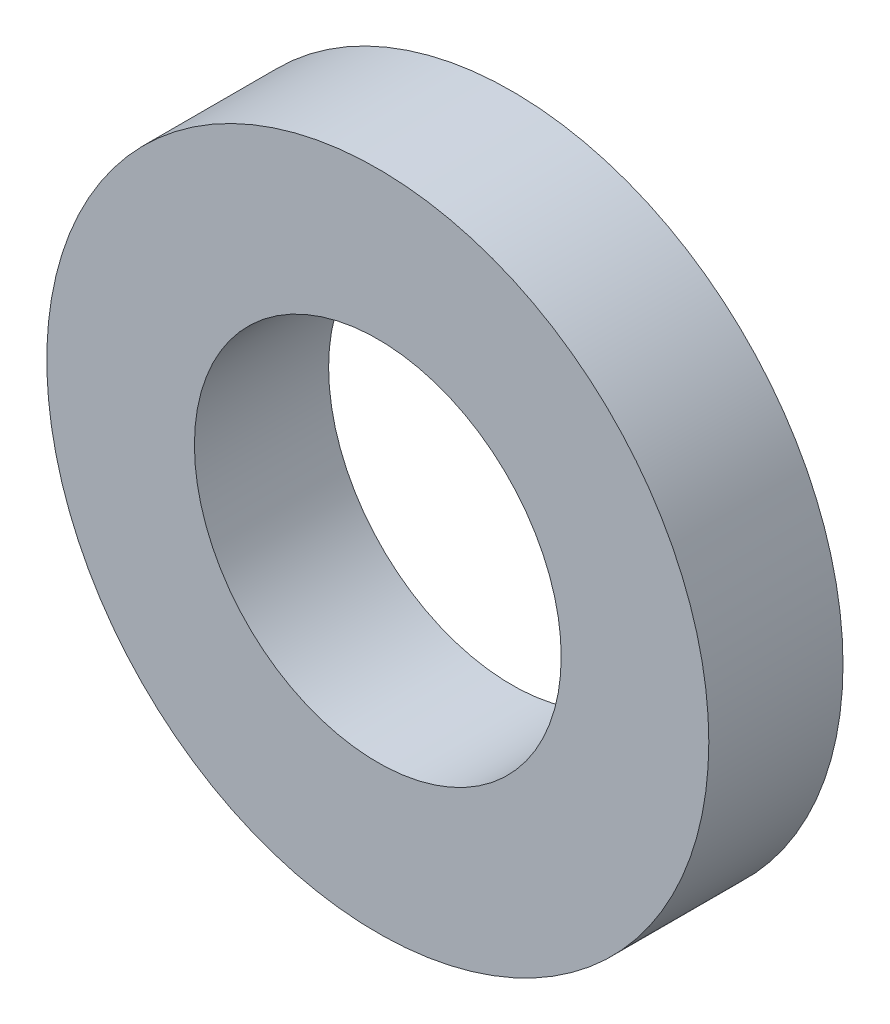
SolidWorks part; units mm, degrees
material "PET"
ref_plane "Piano frontale" through (0, 0, 0) normal (0, 0, 1) x (1, 0, 0)
ref_plane "Piano superiore" through (0, 0, 0) normal (0, 1, 0) x (1, 0, 0)
ref_plane "Piano destro" through (0, 0, 0) normal (1, 0, 0) x (0, 0, -1)
sketch "Schizzo1" plane through (0, 0, 0) normal (0, 0, 1) x (1, 0, 0)
  circle A0 centre (0, 0) radius 4.1
  circle A1 centre (0, 0) radius 7.4
  dimension "D1" = 8.2
  dimension "D2" = 14.8
extrude "Estrusione-Estrusione1" add sketch "Schizzo1" along normal blind 3
